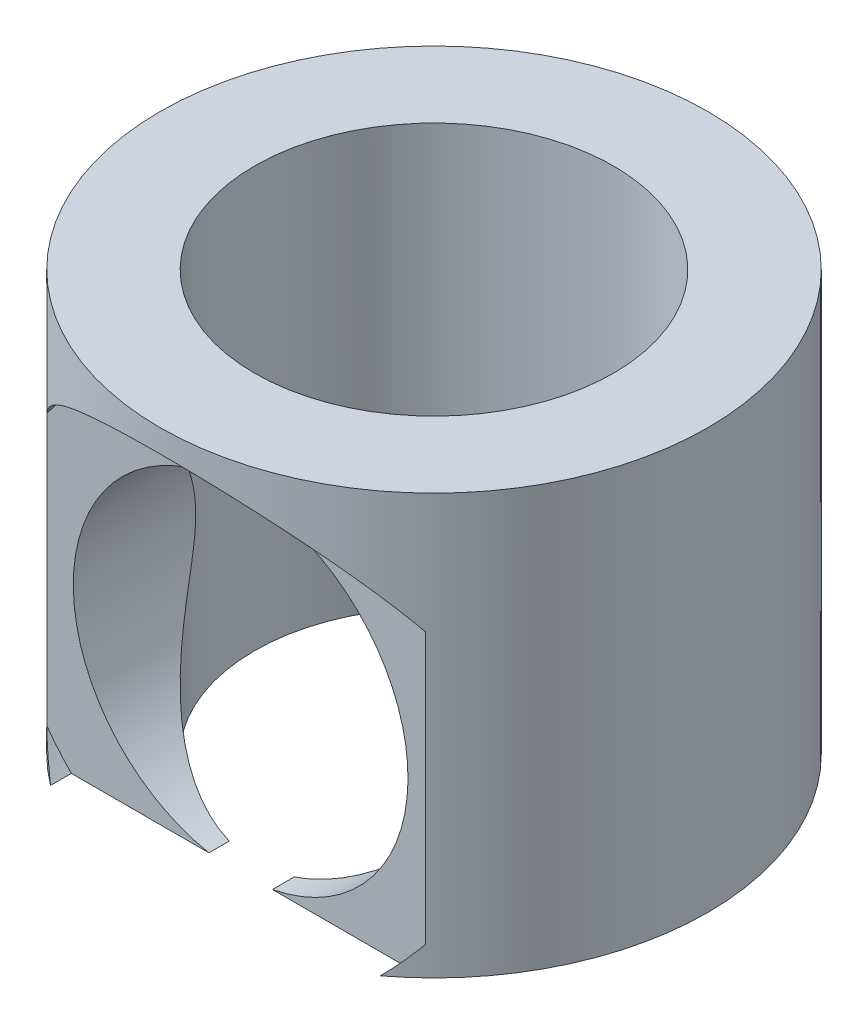
SolidWorks part; units mm, degrees
material "OMD-98"
ref_plane "Front Plane" through (0, 0, 0) normal (0, 0, 1) x (1, 0, 0)
ref_plane "Top Plane" through (0, 0, 0) normal (0, 1, 0) x (1, 0, 0)
ref_plane "Right Plane" through (0, 0, 0) normal (1, 0, 0) x (0, 0, -1)
sketch "Sketch1" plane through (0, 0, 0) normal (0, 1, 0) x (1, 0, 0)
  circle A0 centre (0, 0) radius 9
  circle A1 centre (0, 0) radius 5.9
  dimension "D1" = 18
  dimension "D2" = 11.8
extrude "Boss-Extrude1" add sketch "Sketch1" against normal blind 19.8
sketch "Sketch3" plane through (0, 0, 0) normal (0, 0, 1) x (1, 0, 0)
  line L1 (5.9, 0) -> (-5.9, 0) construction
  circle A0 centre (0, -8.4) radius 7.65
  dimension "D1" = 15.3
  dimension "D2" = 8.4
extrude "Cut-Extrude5" cut sketch "Sketch3" along normal through all from offset 6.5
sketch "Sketch6" plane through (0, 0, 6.5) normal (0, 0, 1) x (1, 0, 0)
  line L0 (-6.2249, -19.8) -> (6.2249, -19.8) construction
  line L1 (6.2249, 0) -> (6.2249, -19.8) construction
  circle A0 centre (0.1455, -8.4) radius 5.5
  dimension "D1" = 11
  dimension "D2" = 11.4
  dimension "D3" = 6.0795
extrude "Cut-Extrude6" cut sketch "Sketch6" against normal blind 7 and the other way through all
ref_plane "Plane1" through (0, -13.8, 0) normal (0, -1, 0) x (-1, 0, 0)
sketch "Sketch7" plane through (0, -13.8, 0) normal (0, -1, 0) x (-1, 0, 0)
  circle A0 centre (0, 0) radius 12.9328
extrude "Cut-Extrude7" cut sketch "Sketch7" along normal blind 10
